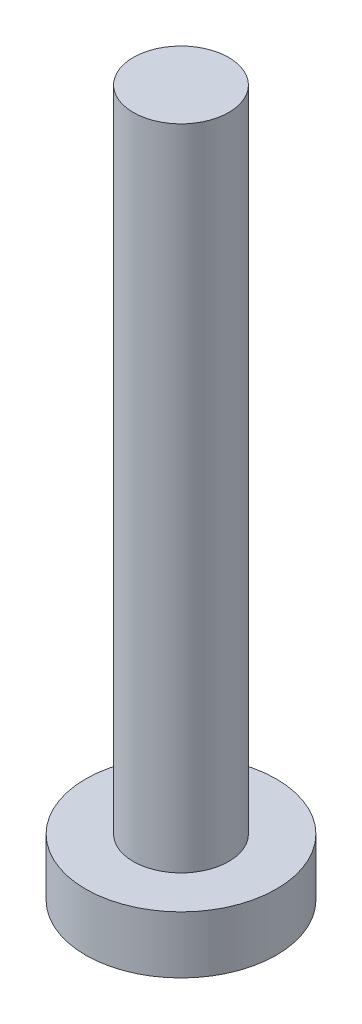
SolidWorks part; units mm, degrees
ref_plane "Front Plane" through (0, 0, 0) normal (0, 0, 1) x (1, 0, 0)
ref_plane "Top Plane" through (0, 0, 0) normal (0, 1, 0) x (1, 0, 0)
ref_plane "Right Plane" through (0, 0, 0) normal (1, 0, 0) x (0, 0, -1)
other "Default"
sketch "Sketch1" plane through (0, 0, 0) normal (0, 1, 0) x (1, 0, 0)
  circle A0 centre (0, 0) radius 2.5
  dimension "Diameter" = 5
extrude "Boss-Extrude1" add sketch "Sketch1" along normal blind 34
sketch "Sketch2" plane through (0, 0, 0) normal (0, -1, 0) x (1, 0, 0)
  circle A0 centre (0, 0) radius 5
  dimension "HeadDiameter" = 10
extrude "Boss-Extrude2" add sketch "Sketch2" along normal blind 3
